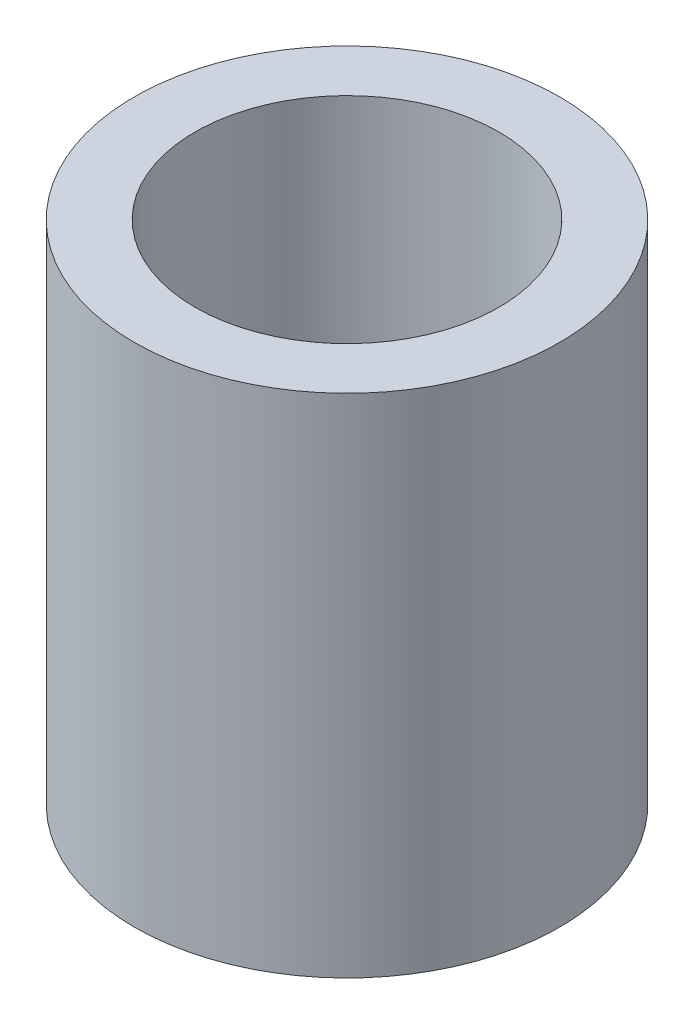
SolidWorks part; units mm, degrees
ref_plane "Спереди" through (0, 0, 0) normal (0, 0, 1) x (1, 0, 0)
ref_plane "Сверху" through (0, 0, 0) normal (0, 1, 0) x (1, 0, 0)
ref_plane "Справа" through (0, 0, 0) normal (1, 0, 0) x (0, 0, -1)
sketch "Эскиз1" plane through (0, 0, 0) normal (0, 1, 0) x (1, 0, 0)
  circle A0 centre (0, 0) radius 1.5
  circle A1 centre (0, 0) radius 2.1
  dimension "D1" = 3
  dimension "D2" = 4.2
extrude "Бобышка-Вытянуть1" add sketch "Эскиз1" along normal blind 5
